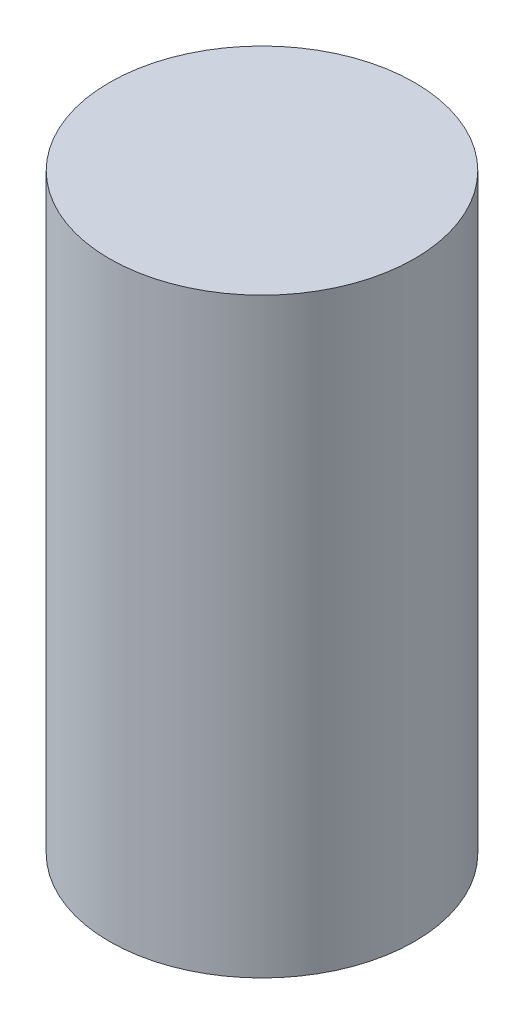
SolidWorks part; units mm, degrees
ref_plane "Front Plane" through (0, 0, 0) normal (0, 0, 1) x (1, 0, 0)
ref_plane "Top Plane" through (0, 0, 0) normal (0, 1, 0) x (1, 0, 0)
ref_plane "Right Plane" through (0, 0, 0) normal (1, 0, 0) x (0, 0, -1)
sketch "Sketch1" plane through (0, 0, 0) normal (0, 1, 0) x (1, 0, 0)
  circle A0 centre (0, 0) radius 8
  dimension "D1" = 16
extrude "Boss-Extrude1" add sketch "Sketch1" along normal blind 31
